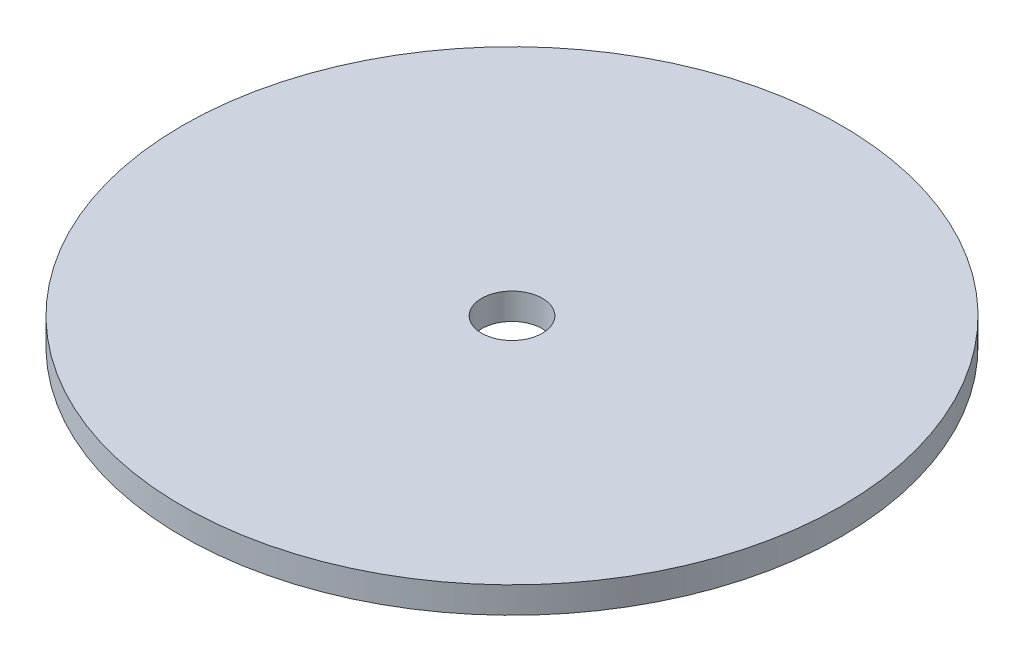
SolidWorks part; units mm, degrees
ref_plane "Front Plane" through (0, 0, 0) normal (0, 0, 1) x (1, 0, 0)
ref_plane "Top Plane" through (0, 0, 0) normal (0, 1, 0) x (1, 0, 0)
ref_plane "Right Plane" through (0, 0, 0) normal (1, 0, 0) x (0, 0, -1)
sketch "Sketch1" plane through (0, -0.7994, 0) normal (0, -1, 0) x (1, 0, 0)
  circle A0 centre (0, 0) radius 37.5
  dimension "D1" = 75
extrude "Boss-Extrude1" add sketch "Sketch1" along normal blind 3
sketch "Sketch2" plane through (0, -0.7994, 0) normal (0, 1, 0) x (1, 0, 0)
  line L0 (0, 0) -> (0, 25) construction
  circle A0 centre (0, 0) radius 7.5 construction
  point P4 (0, 0)
  dimension "D2" = 15
  dimension "D1" = 25
sketch "Sketch3" plane through (0, -3.7994, 0) normal (0, -1, 0) x (1, 0, 0)
  circle A0 centre (0, 0) radius 3.45 construction
  circle A1 centre (0, 0) radius 3.45
extrude "Cut-Extrude1" cut sketch "Sketch3" against normal up to next
